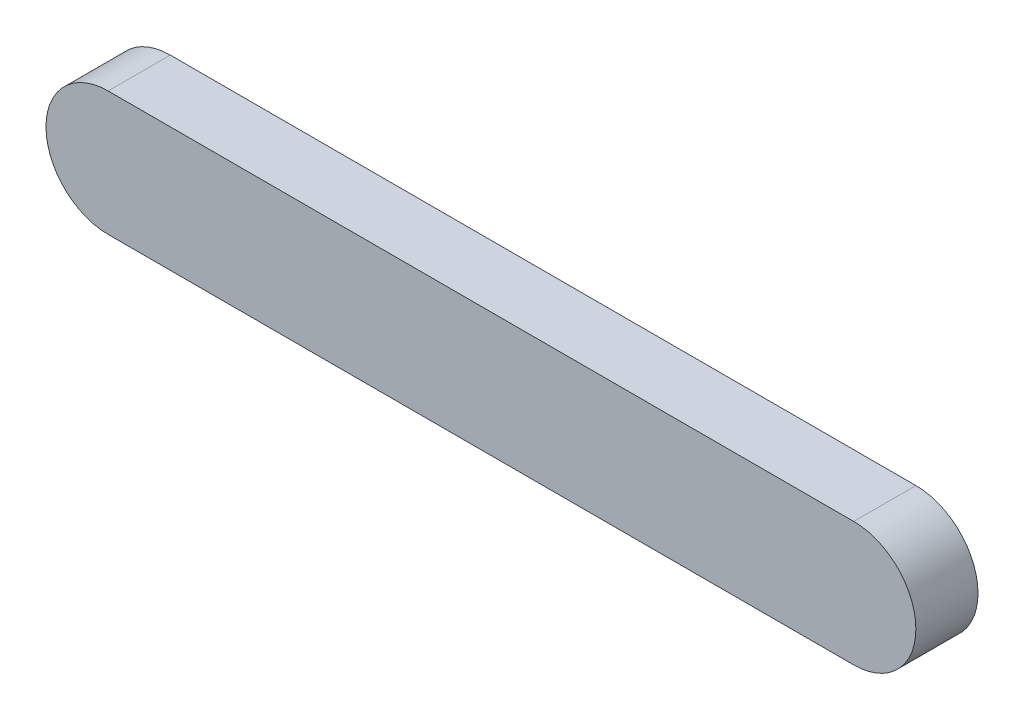
SolidWorks part; units mm, degrees
ref_plane "前视基准面" through (0, 0, 0) normal (0, 0, 1) x (1, 0, 0)
ref_plane "上视基准面" through (0, 0, 0) normal (0, 1, 0) x (1, 0, 0)
ref_plane "右视基准面" through (0, 0, 0) normal (1, 0, 0) x (0, 0, -1)
sketch "草图1" plane through (0, 0, 0) normal (0, 0, 1) x (1, 0, 0)
  line L0 (0, 0) -> (120, 0) construction
  line L1 (0, 10) -> (120, 10)
  line L2 (0, -10) -> (120, -10)
  arc A2 (0, 10) -> (0, -10) centre (0, 0) ccw
  arc A3 (120, -10) -> (120, 10) centre (120, 0) ccw
  point P3 (60, 0)
  dimension "D2" = 20
  dimension "D1" = 120
extrude "凸台-拉伸1" add sketch "草图1" along normal blind 10
